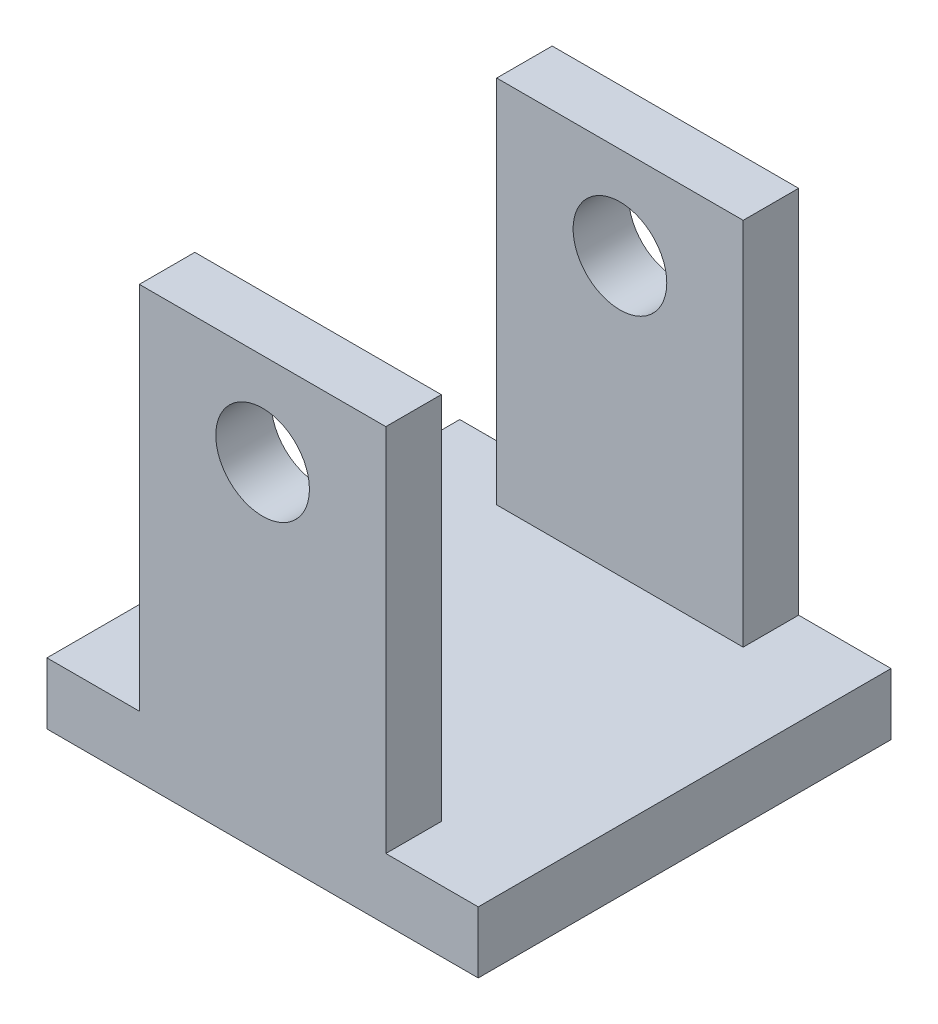
SolidWorks part; units mm, degrees
ref_plane "Front Plane" through (0, 0, 0) normal (0, 0, 1) x (1, 0, 0)
ref_plane "Top Plane" through (0, 0, 0) normal (0, 1, 0) x (1, 0, 0)
ref_plane "Right Plane" through (0, 0, 0) normal (1, 0, 0) x (0, 0, -1)
sketch "Sketch2" plane through (0, 0, 0) normal (0, 0, 1) x (1, 0, 0)
  line L0 (0, 0) -> (0, -110) construction
  line L1 (-35, -45) -> (35, -45)
  line L2 (-35, -45) -> (-35, -55)
  line L3 (-35, -55) -> (35, -55)
  line L4 (35, -45) -> (35, -55)
  point P7 (0, -55)
  dimension "D1" = 70
  dimension "D2" = 10
  dimension "D3" = 55
extrude "Boss-Extrude1" add sketch "Sketch2" along normal mid plane 67
sketch "Sketch3" plane through (0, 0, 0) normal (0, 0, 1) x (1, 0, 0)
  line L0 (0, 46.0656) -> (0, -76.8036) construction
  line L1 (-20, 15) -> (20, 15)
  line L2 (-20, 15) -> (-20, -45)
  line L3 (-20, -45) -> (20, -45)
  line L4 (20, 15) -> (20, -45)
  line L5 (35, -45) -> (-35, -45) construction
  point P9 (0, 15)
  dimension "D1" = 40
  dimension "D2" = 60
  dimension "D3" = 0
extrude "Boss-Extrude2" add sketch "Sketch3" along normal mid plane 67
sketch "Sketch4" plane through (0, 0, 0) normal (0, 0, 1) x (1, 0, 0)
  line L0 (-20, -45) -> (-35, -45) construction
  line L1 (-20, 15) -> (20, 15)
  line L2 (-20, 15) -> (-20, -45)
  line L3 (-20, -45) -> (20, -45)
  line L4 (20, 15) -> (20, -45)
  point P7 (0, 15)
  dimension "D1" = 40
  dimension "D2" = 60
  dimension "D3" = 0
extrude "Cut-Extrude1" cut sketch "Sketch4" against normal mid plane 49
sketch "Sketch5" plane through (0, 0, 0) normal (0, 0, 1) x (1, 0, 0)
  circle A0 centre (0, 0) radius 7.6
  dimension "D1" = 15.2
extrude "Cut-Extrude2" cut sketch "Sketch5" against normal through all both and the other way through all
